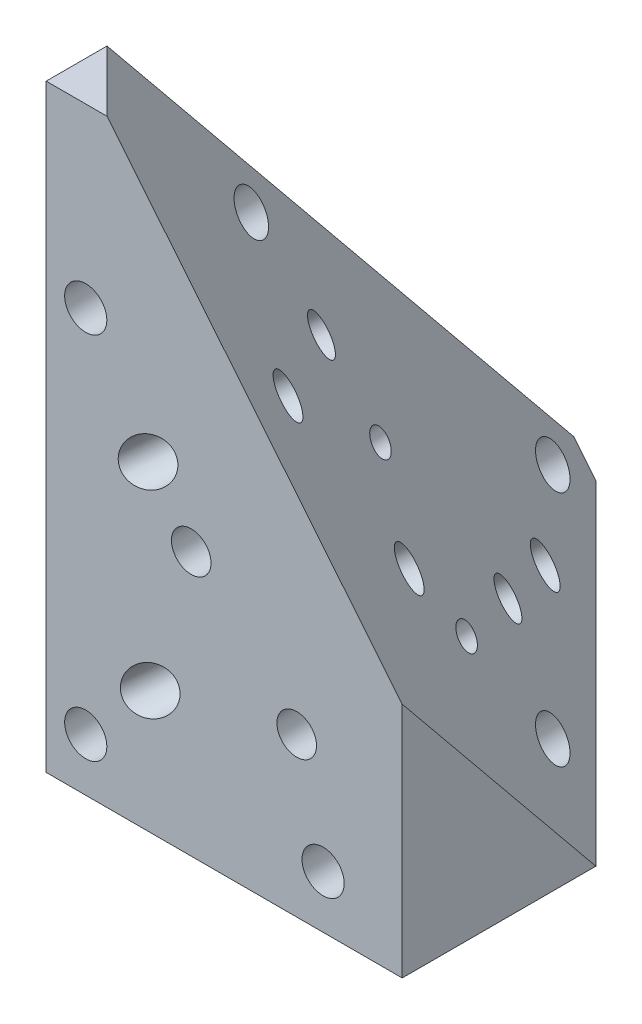
SolidWorks part; units mm, degrees
ref_plane "Front Plane" through (0, 0, 0) normal (0, 0, 1) x (1, 0, 0)
ref_plane "Top Plane" through (0, 0, 0) normal (0, 1, 0) x (1, 0, 0)
ref_plane "Right Plane" through (0, 0, 0) normal (1, 0, 0) x (0, 0, -1)
sketch "Sketch1" plane through (0, 0, 0) normal (0, 1, 0) x (1, 0, 0)
  line L0 (0, 0) -> (0, 20)
  line L2 (13.5, 0) -> (0, 0)
  line L3 (0, 20) -> (13.5, 20)
  line L4 (13.5, 20) -> (13.5, 0)
  dimension "D1" = 13.5
  dimension "D2" = 20
extrude "Boss-Extrude1" add sketch "Sketch1" along normal blind 22.7
ref_plane "Plane1" through (7.8154, 6.3813, -7.8154) normal (-0.6124, -0.5, 0.6124) x (0.7906, -0.3873, 0.4743)
sketch "Sketch2" plane through (7.8154, 6.3813, -7.8154) normal (-0.6124, -0.5, 0.6124) x (0.7906, -0.3873, 0.4743)
  line L1 (25.0062, -28.8765) -> (-25.0062, -28.8765)
  line L2 (25.0062, -28.8765) -> (25.0062, 28.8765)
  line L3 (25.0062, 28.8765) -> (-25.0062, 28.8765)
  line L4 (-25.0062, -28.8765) -> (-25.0062, 28.8765)
  line L5 (25.0062, -28.8765) -> (-25.0062, 28.8765) construction
  line L6 (25.0062, 28.8765) -> (-25.0062, -28.8765) construction
  point P0 (0, 0)
extrude "Cut-Extrude1" cut sketch "Sketch2" against normal through all
ref_plane "Plane2" through (-5.5147, 0, -5.5147) normal (-0.7071, 0, -0.7071) x (-0.7071, 0, 0.7071)
sketch "Sketch4" plane through (7.8154, 6.3813, -7.8154) normal (0.6124, 0.5, -0.6124) x (-0.4743, -0.3873, -0.7906)
  circle A0 centre (7.7161, -1.3471) radius 0.8 construction
  circle A1 centre (7.7161, -1.3471) radius 0.8 construction
  circle A2 centre (-6.5295, 6.9513) radius 0.8 construction
  circle A3 centre (-3.675, 1.1117) radius 0.8 construction
  circle A4 centre (-6.5295, 6.9513) radius 0.8 construction
  circle A5 centre (-3.675, 1.1117) radius 0.8 construction
hole_wizard "M2x0.4 Tapped Hole1" positions "3DSketch1" profile "Sketch5" tap size "M2x0.4" standard "ANSI Metric" end condition through all
sketch3d "3DSketch1"
  point P0 (6.5162, 14.2946, -2.6534)
  point P3 (8.8555, 8.6657, -4.9101)
  point P6 (5.0074, 2.3494, -13.9155)
sketch "Sketch5" plane through (6.5162, 14.2946, -2.6534) normal (0.4344, 0.4344, 0.7891) x (-0.6605, 0.7492, -0.0488)
  line L0 (0, 0) -> (0, 12.7625)
  line L1 (0, 12.7625) -> (0.8, 12.7625)
  line L2 (0.8, 12.7625) -> (0.8, 0)
  line L5 (0.8, 0) -> (0, 0)
  line L11 (0, -6.35) -> (0, 107.95) construction
  dimension "Thru Tap Drill Dia." = 1.6
  dimension "Thru Tap Drill Depth" = 12.7625
cosmetic thread "Hole Thread1" parameters "D2"=2
cosmetic thread "Hole Thread2" parameters "D2"=2
cosmetic thread "Hole Thread3" parameters "D2"=2
sketch "Sketch7" plane through (0, 0, 0) normal (0, 0, 1) x (1, 0, 0)
  circle A0 centre (10.5, 2) radius 1.2 construction
  circle A1 centre (10.5, 2) radius 1.2 construction
  circle A2 centre (1.5, 2) radius 1.2 construction
  circle A3 centre (1.5, 2) radius 1.2 construction
  circle A4 centre (1.5, 16) radius 1.2 construction
  circle A5 centre (1.5, 16) radius 1.2
hole_wizard "M2x0.4 Tapped Hole3" positions "3DSketch3" profile "Sketch9" tap size "M2x0.4" standard "ANSI Metric" end condition through all
sketch3d "3DSketch3"
  point P0 (1.5, 16, 0)
  point P3 (1.5, 2, 0)
  point P6 (10.5, 2, 0)
sketch "Sketch9" plane through (1.5, 16, 0) normal (1, 0, 0) x (0, -1, 0)
  line L0 (0, 0) -> (0, 20)
  line L1 (0, 20) -> (0.8, 20)
  line L2 (0.8, 20) -> (0.8, 0)
  line L5 (0.8, 0) -> (0, 0)
  line L11 (0, -6.35) -> (0, 107.95) construction
  dimension "Thru Tap Drill Dia." = 1.6
  dimension "Thru Tap Drill Depth" = 20
cosmetic thread "Hole Thread7" parameters "D1"=2.4, "D2"=2
cosmetic thread "Hole Thread8" parameters "D1"=2.4, "D2"=2
cosmetic thread "Hole Thread9" parameters "D1"=2.4, "D2"=2
sketch "Sketch10" plane through (0, 0, 0) normal (0, 0, 1) x (1, 0, 0)
  circle A0 centre (5.5, 10) radius 0.5 construction
  circle A1 centre (9.5, 6) radius 0.5 construction
  circle A2 centre (5.5, 10) radius 0.5 construction
  circle A3 centre (9.5, 6) radius 0.5 construction
hole_wizard "Ø1.0mm Dowel Hole1" positions "3DSketch4" profile "Sketch11" hole size "Ø1.0" standard "ANSI Metric" end condition through all
sketch3d "3DSketch4"
  point P0 (5.5, 10, 0)
  point P3 (9.5, 6, 0)
sketch "Sketch11" plane through (5.5, 10, 0) normal (1, 0, 0) x (0, -1, 0)
  line L0 (0, 0) -> (0, 20)
  line L1 (0, 20) -> (0.5, 20)
  line L2 (0.5, 20) -> (0.5, 0)
  line L5 (0.5, 0) -> (0, 0)
  line L11 (0, -6.35) -> (0, 107.95) construction
  dimension "Thru Hole Dia." = 1
  dimension "Thru Hole Depth" = 20
hole_wizard "Ø1.5mm Dowel Hole1" positions "3DSketch5" profile "Sketch13" hole size "Ø1.5" standard "ANSI Metric"
sketch3d "3DSketch5"
  point P0 (5.5, 10, 0)
  point P3 (9.5, 6, 0)
sketch "Sketch13" plane through (5.5, 10, 0) normal (1, 0, 0) x (0, -1, 0)
  line L0 (0, 0) -> (0, 4.9506)
  line L1 (0, 4.9506) -> (0.75, 4.5)
  line L2 (0.75, 4.5) -> (0.75, 0)
  line L5 (0.75, 0) -> (0, 0)
  line L10 (0, 4.9506) -> (-0.75, 4.5) construction
  line L11 (0, -6.35) -> (0, 107.95) construction
  dimension "Hole Dia." = 1.5
  dimension "Hole Depth" = 4.5
  dimension "Drill Angle" = 118
sketch "Sketch14" plane through (7.8154, 6.3813, -7.8154) normal (0.6124, 0.5, -0.6124) x (-0.4743, -0.3873, -0.7906)
  circle A0 centre (-1.2282, 7.5971) radius 0.75 construction
  circle A1 centre (3.2439, -1.3471) radius 0.75 construction
  circle A2 centre (-1.2282, 7.5971) radius 0.75 construction
  circle A3 centre (3.2439, -1.3471) radius 0.75 construction
hole_wizard "Ø1.0mm Dowel Hole2" positions "3DSketch6" profile "Sketch15" hole size "Ø1.0" standard "ANSI Metric" end condition through all
sketch3d "3DSketch6"
  point P0 (3.5932, 12.7417, -6.8444)
  point P3 (7.1287, 4.0814, -10.38)
sketch "Sketch15" plane through (3.5932, 12.7417, -6.8444) normal (0.4344, 0.4344, 0.7891) x (-0.6605, 0.7492, -0.0488)
  line L0 (0, 0) -> (0, 12.7625)
  line L1 (0, 12.7625) -> (0.5, 12.7625)
  line L2 (0.5, 12.7625) -> (0.5, 0)
  line L5 (0.5, 0) -> (0, 0)
  line L11 (0, -6.35) -> (0, 107.95) construction
  dimension "Thru Hole Dia." = 1
  dimension "Thru Hole Depth" = 12.7625
hole_wizard "Ø1.5mm Dowel Hole2" positions "3DSketch7" profile "Sketch16" hole size "Ø1.5" standard "ANSI Metric"
sketch3d "3DSketch7"
  point P0 (3.5932, 12.7417, -6.8444)
  point P3 (7.1287, 4.0814, -10.38)
sketch "Sketch16" plane through (3.5932, 12.7417, -6.8444) normal (0.4344, 0.4344, 0.7891) x (-0.6605, 0.7492, -0.0488)
  line L0 (0, 0) -> (0, 3.9506)
  line L1 (0, 3.9506) -> (0.75, 3.5)
  line L2 (0.75, 3.5) -> (0.75, 0)
  line L5 (0.75, 0) -> (0, 0)
  line L10 (0, 3.9506) -> (-0.75, 3.5) construction
  line L11 (0, -6.35) -> (0, 107.95) construction
  dimension "Hole Dia." = 1.5
  dimension "Hole Depth" = 3.5
  dimension "Drill Angle" = 118
